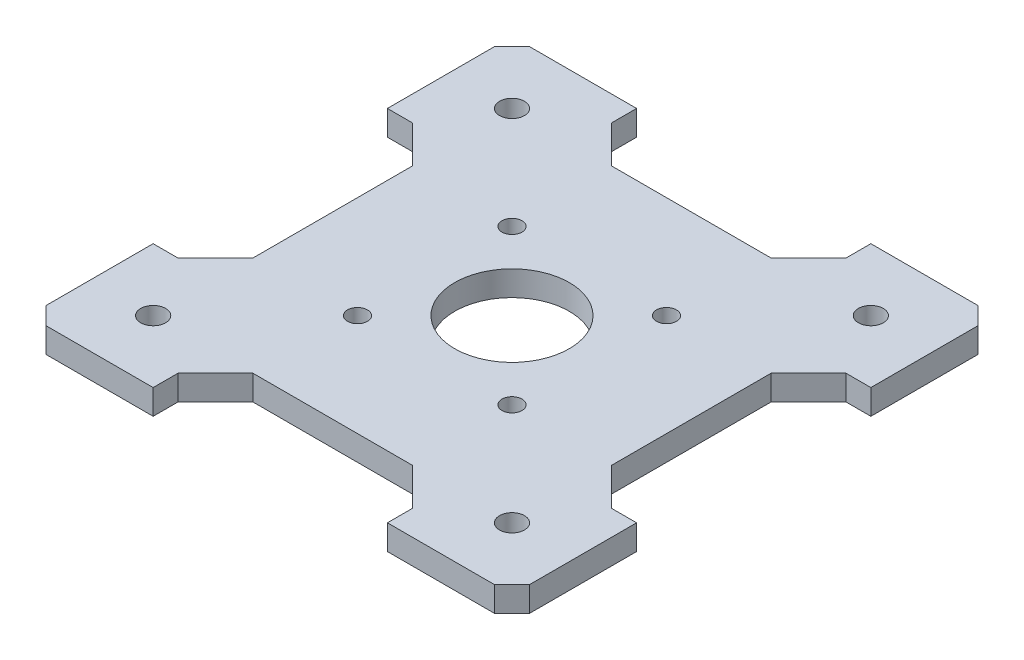
SolidWorks part; units mm, degrees
material "Alumina"
ref_plane "Front Plane" through (0, 0, 0) normal (0, 0, 1) x (1, 0, 0)
ref_plane "Top Plane" through (0, 0, 0) normal (0, 1, 0) x (1, 0, 0)
ref_plane "Right Plane" through (0, 0, 0) normal (1, 0, 0) x (0, 0, -1)
sketch "Sketch1" plane through (0, 0, 0) normal (0, 1, 0) x (1, 0, 0)
  line L1 (-36, 36) -> (36, 36)
  line L2 (-36, 36) -> (-36, -36)
  line L3 (-36, -36) -> (36, -36)
  line L4 (36, 36) -> (36, -36)
  line L5 (-36, 36) -> (36, -36) construction
  line L6 (-36, -36) -> (36, 36) construction
  point P0 (0, 0)
  dimension "D1" = 72
  dimension "D2" = 72
extrude "Boss-Extrude1" add sketch "Sketch1" along normal blind 5
sketch "Sketch5" plane through (0, 5, 0) normal (0, 1, 0) x (1, 0, 0)
  line L0 (0, 36) -> (0, -36) construction
  line L1 (-48.5, -23.5) -> (-23.5, -23.5)
  line L2 (-48.5, -23.5) -> (-48.5, -48.5)
  line L3 (-48.5, -48.5) -> (-23.5, -48.5)
  line L4 (-23.5, -23.5) -> (-23.5, -48.5)
  line L5 (-48.5, -23.5) -> (-23.5, -48.5) construction
  line L6 (-48.5, -48.5) -> (-23.5, -23.5) construction
  line L7 (36, 36) -> (-36, 36) construction
  line L8 (-36, -36) -> (36, -36) construction
  line L9 (-36, 0) -> (36, 0) construction
  line L10 (-36, 36) -> (-36, -36) construction
  line L11 (36, -36) -> (36, 36) construction
  line L12 (23.5, -23.5) -> (23.5, -48.5)
  line L13 (48.5, -48.5) -> (23.5, -48.5)
  line L14 (48.5, -23.5) -> (48.5, -48.5)
  line L15 (48.5, -23.5) -> (23.5, -23.5)
  line L16 (48.5, 23.5) -> (48.5, 48.5)
  line L17 (48.5, 23.5) -> (23.5, 23.5)
  line L18 (23.5, 23.5) -> (23.5, 48.5)
  line L19 (48.5, 48.5) -> (23.5, 48.5)
  line L20 (-23.5, 23.5) -> (-23.5, 48.5)
  line L21 (-48.5, 48.5) -> (-23.5, 48.5)
  line L22 (-48.5, 23.5) -> (-48.5, 48.5)
  line L23 (-48.5, 23.5) -> (-23.5, 23.5)
  point P0 (-36, -36)
  dimension "D1" = 25
extrude "Boss-Extrude2" add sketch "Sketch5" against normal up to surface (5 mm away) up to face at (0, 0, 0)
sketch "Sketch3" plane through (0, 5, 0) normal (0, 1, 0) x (1, 0, 0)
  line L0 (-48.5, -36) -> (-23.5, -36) construction
  line L1 (-48.5, -23.5) -> (-48.5, -48.5) construction
  line L2 (-36, -23.5) -> (-36, -48.5) construction
  line L3 (-36, -23.5) -> (-48.5, -23.5) construction
  line L4 (-48.5, -48.5) -> (-23.5, -48.5) construction
  line L5 (0, 36) -> (0, -36) construction
  line L6 (23.5, 36) -> (-23.5, 36) construction
  line L7 (-36, 0) -> (36, 0) construction
  line L8 (-36, 23.5) -> (-36, -23.5) construction
  line L9 (36, -23.5) -> (36, 23.5) construction
  line L10 (-23.5, -36) -> (23.5, -36) construction
  circle A0 centre (-15.5, 15.5) radius 2
  circle A1 centre (15.5, 15.5) radius 2
  circle A2 centre (15.5, -15.5) radius 2
  circle A3 centre (-15.5, -15.5) radius 2
  circle A4 centre (0, 0) radius 11.5
  circle A5 centre (-36, -36) radius 2.5
  circle A6 centre (36, -36) radius 2.5
  circle A7 centre (36, 36) radius 2.5
  circle A8 centre (-36, 36) radius 2.5
  dimension "D1" = 4
  dimension "D8" = 23
  dimension "D9" = 5
  dimension "D2" = 15.5
  dimension "D3" = 15.5
  dimension "D6" = 31
  dimension "D7" = 31
  dimension "D4" = 2
  dimension "D5" = 2
extrude "Cut-Extrude1" cut sketch "Sketch3" against normal through all
chamfer "Chamfer1" distance 7.5 angle 45 8 edges at (-36, 2.5, 23.5) (-36, 2.5, -23.5) (-23.5, 2.5, -36) (23.5, 2.5, -36) (36, 2.5, -23.5) (36, 2.5, 23.5) (23.5, 2.5, 36) (-23.5, 2.5, 36)
chamfer "Chamfer2" distance 3.5 angle 45 4 edges at (-48.5, 2.5, -48.5) (48.5, 2.5, -48.5) (48.5, 2.5, 48.5) (-48.5, 2.5, 48.5)
equation "\"Stepper Motor Width\"= 42mm"
equation "\"Stepper Motor Length\"= 42mm"
equation "\"Extra Spacing\"= 15mm"
equation "\"Plate Thickness\"= 5mm"
equation "\"Screw X-Offset\"= 15.5mm"
equation "\"Screw Y-Offset\"= 15.5mm"
equation "\"D1@Sketch1\"=\"Stepper Motor Width\"+\"Extra Spacing\"*2"
equation "\"D2@Sketch1\"=\"Stepper Motor Length\"+\"Extra Spacing\"*2"
equation "\"D1@Boss-Extrude1\"=\"Plate Thickness\""
equation "\"Stepper Screw Diameter\"= 4mm"
equation "\"D6@Sketch3\"=\"Screw X-Offset\"*2"
equation "\"Shaft Diameter\"= 23mm"
equation "\"D8@Sketch3\"=\"Shaft Diameter\""
equation "\"Plate Mount Screw Diameter\"= 5mm"
equation "\"D9@Sketch3\"=\"Plate Mount Screw Diameter\""
